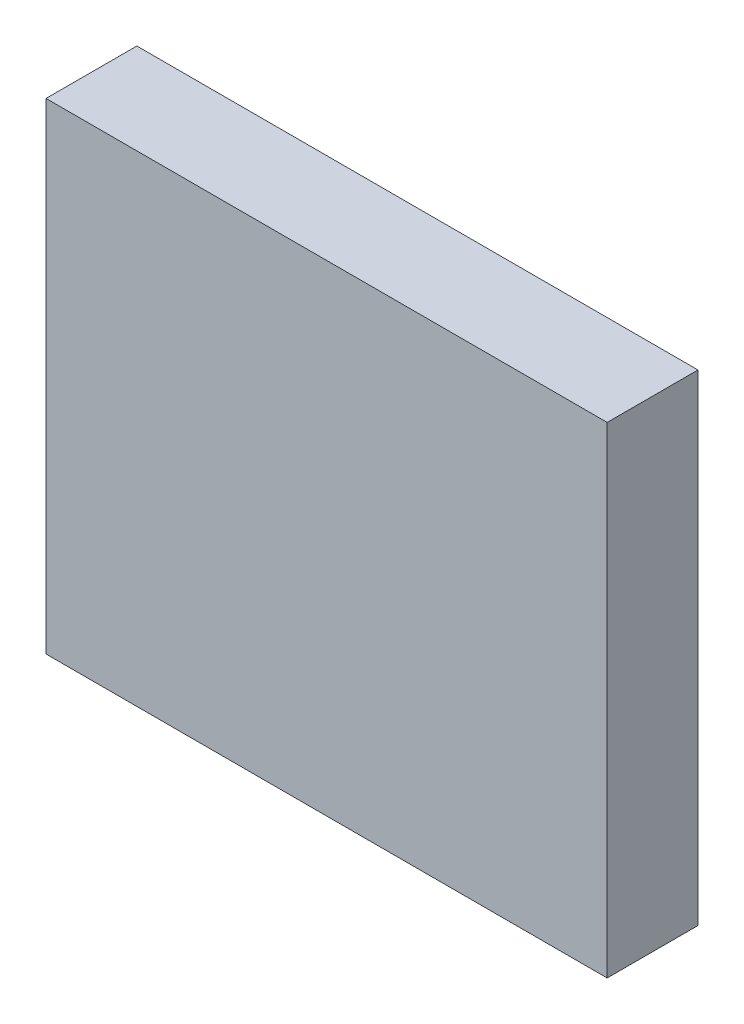
SolidWorks part; units mm, degrees
ref_plane "Front" through (0, 0, 0) normal (0, 0, 1) x (1, 0, 0)
ref_plane "Top" through (0, 0, 0) normal (0, 1, 0) x (1, 0, 0)
ref_plane "Right" through (0, 0, 0) normal (1, 0, 0) x (0, 0, -1)
sketch "Esboço1" plane through (0, 0, 0) normal (0, 0, 1) x (1, 0, 0)
  line L1 (-30.896, 26.4925) -> (30.896, 26.4925)
  line L2 (-30.896, 26.4925) -> (-30.896, -26.4925)
  line L3 (-30.896, -26.4925) -> (30.896, -26.4925)
  line L4 (30.896, 26.4925) -> (30.896, -26.4925)
  line L5 (-30.896, 26.4925) -> (30.896, -26.4925) construction
  line L6 (-30.896, -26.4925) -> (30.896, 26.4925) construction
  point P0 (0, 0)
extrude "Ressalto-extrusão1" add sketch "Esboço1" along normal mid plane 10
